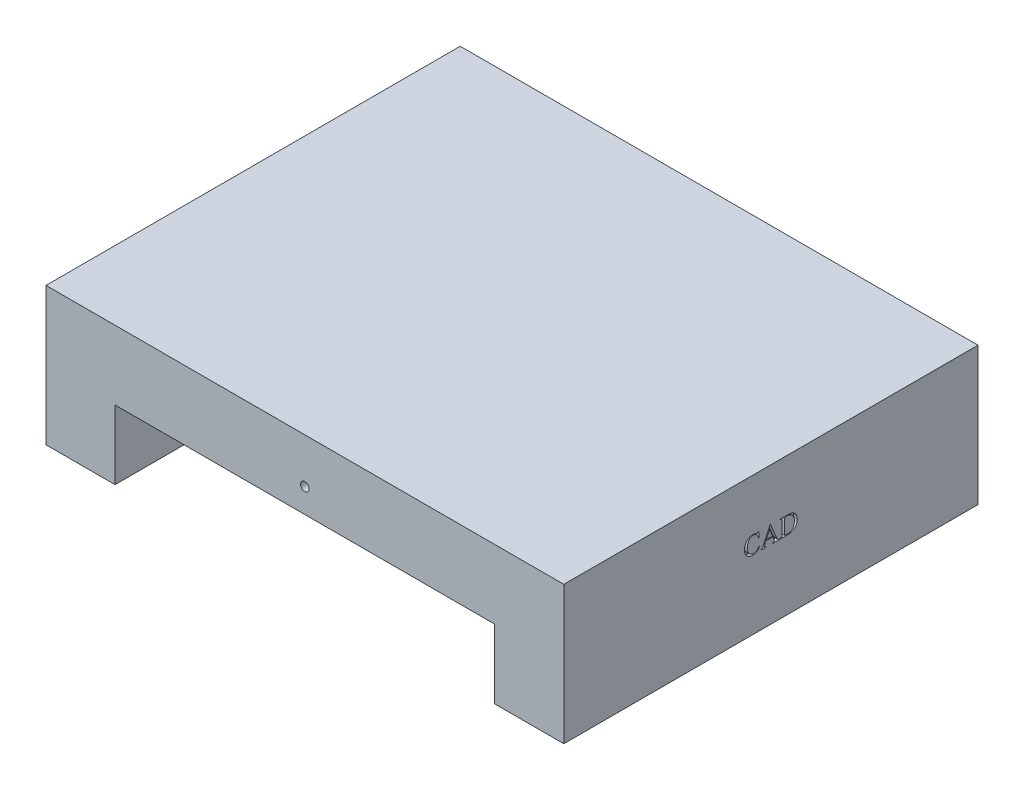
SolidWorks part; units mm, degrees
ref_plane "Front Plane" through (0, 0, 0) normal (0, 0, 1) x (1, 0, 0)
ref_plane "Top Plane" through (0, 0, 0) normal (0, 1, 0) x (1, 0, 0)
ref_plane "Right Plane" through (0, 0, 0) normal (1, 0, 0) x (0, 0, -1)
sketch "Sketch1" plane through (0, 0, 0) normal (0, 0, 1) x (1, 0, 0)
  line L1 (-75, 20) -> (75, 20)
  line L2 (-75, 20) -> (-75, -20)
  line L3 (-75, -20) -> (75, -20)
  line L4 (75, 20) -> (75, -20)
  line L5 (-75, 20) -> (75, -20) construction
  line L6 (-75, -20) -> (75, 20) construction
  point P0 (0, 0)
  dimension "D1" = 150
  dimension "D2" = 40
extrude "Boss-Extrude1" add sketch "Sketch1" along normal mid plane 120
sketch "Sketch2" plane through (0, 0, 60) normal (0, 0, 1) x (1, 0, 0)
  line L0 (-75, -20) -> (75, -20) construction
  line L1 (-55, -20) -> (55, -20)
  line L2 (-55, -20) -> (-55, 0)
  line L3 (-55, 0) -> (55, 0)
  line L4 (55, -20) -> (55, 0)
  line L5 (-55, -20) -> (55, 0) construction
  line L6 (-55, 0) -> (55, -20) construction
  line L7 (-75, 20) -> (-75, -20) construction
  line L8 (75, -20) -> (75, 20) construction
  point P4 (0, -10)
  dimension "D1" = 20
  dimension "D2" = 20
  dimension "D3" = 20
extrude "Cut-Extrude1" cut sketch "Sketch2" against normal through all
sketch "Sketch3" plane through (0, 0, 60) normal (0, 0, 1) x (1, 0, 0)
  line L0 (55, 0) -> (-55, 0) construction
  circle A0 centre (0, 7) radius 1.25
  dimension "D1" = 2.5
  dimension "D2" = 7
extrude "Cut-Extrude2" cut sketch "Sketch3" against normal blind 5
sketch "Sketch4" plane through (75, 0, 0) normal (1, 0, 0) x (0, 0, -1)
  line L0 (-60, 0) -> (60, 0) construction
  line L1 (-60, -20) -> (-60, 20) construction
  line L2 (60, -20) -> (60, 20) construction
  text T0 "CAD" font "Times New Roman" height 5
extrude "Cut-Extrude3" cut sketch "Sketch4" against normal blind 1
